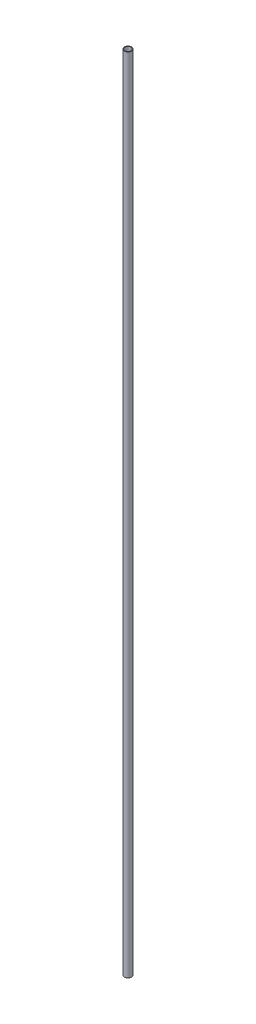
SolidWorks part; units mm, degrees
material "AISI 316 Stainless Steel Sheet (SS)"
ref_plane "Front Plane" through (0, 0, 0) normal (0, 0, 1) x (1, 0, 0)
ref_plane "Top Plane" through (0, 0, 0) normal (0, 1, 0) x (1, 0, 0)
ref_plane "Right Plane" through (0, 0, 0) normal (1, 0, 0) x (0, 0, -1)
sketch "Sketch1" plane through (0, 0, 0) normal (0, 1, 0) x (1, 0, 0)
  circle A0 centre (0, 0) radius 6.35
  circle A1 centre (0, 0) radius 5.35
  dimension "D1" = 12.7
  dimension "D2" = 1
extrude "Boss-Extrude1" add sketch "Sketch1" along normal blind 1399.5
